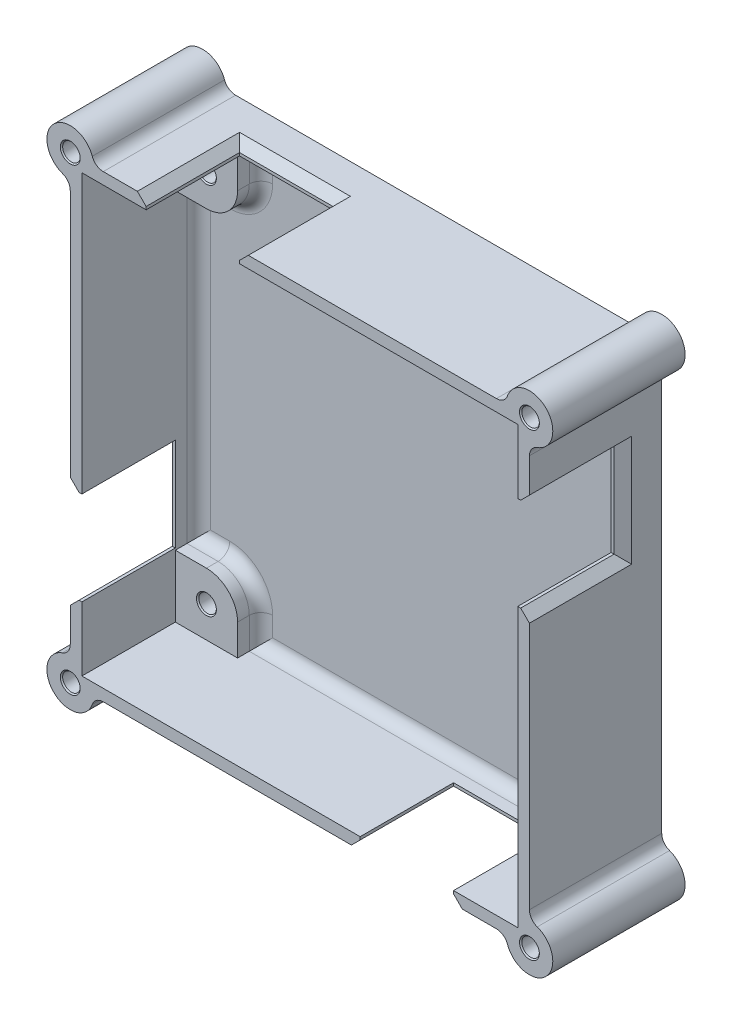
SolidWorks part; units mm, degrees
ref_plane "Front Plane" through (0, 0, 0) normal (0, 0, 1) x (1, 0, 0)
ref_plane "Top Plane" through (0, 0, 0) normal (0, 1, 0) x (1, 0, 0)
ref_plane "Right Plane" through (0, 0, 0) normal (1, 0, 0) x (0, 0, -1)
sketch "Sketch1" plane through (0, 0, 0) normal (0, 0, 1) x (1, 0, 0)
  line L1 (59, 59) -> (-59, 59)
  line L2 (59, 59) -> (59, -59)
  line L3 (59, -59) -> (-59, -59)
  line L4 (-59, 59) -> (-59, -59)
  line L5 (59, 59) -> (-59, -59) construction
  line L6 (59, -59) -> (-59, 59) construction
  point P0 (0, 0)
  dimension "D1" = 118
  dimension "D2" = 118
extrude "Boss-Extrude1" add sketch "Sketch1" against normal blind 4
sketch "Sketch2" plane through (0, 0, 0) normal (0, 0, 1) x (1, 0, 0)
  line L1 (56, 56) -> (-56, 56)
  line L2 (56, 56) -> (56, -56)
  line L3 (56, -56) -> (-56, -56)
  line L4 (-56, 56) -> (-56, -56)
  line L5 (56, 56) -> (-56, -56) construction
  line L6 (56, -56) -> (-56, 56) construction
  line L7 (59, 59) -> (-59, 59)
  line L8 (59, 59) -> (59, -59)
  line L9 (59, -59) -> (-59, -59)
  line L10 (-59, 59) -> (-59, -59)
  line L11 (59, 59) -> (-59, -59) construction
  line L12 (59, -59) -> (-59, 59) construction
  point P0 (0, 0)
  point P6 (0, 0)
  dimension "D1" = 112
  dimension "D2" = 112
extrude "Boss-Extrude2" add sketch "Sketch2" along normal blind 30
sketch "Sketch3" plane through (0, 0, 0) normal (0, 0, 1) x (1, 0, 0)
  line L7 (56, 56) -> (40, 56)
  line L8 (56, 56) -> (56, 40)
  line L9 (56, 40) -> (40, 40)
  line L10 (40, 56) -> (40, 40)
  line L11 (56, 56) -> (40, 40) construction
  line L12 (56, 40) -> (40, 56) construction
  circle A0 centre (48, 48) radius 2.25
  dimension "D1" = 4.5
  dimension "D2" = 48
  dimension "D3" = 48
  dimension "D4" = 16
  dimension "D5" = 16
extrude "Boss-Extrude3" add sketch "Sketch3" along normal blind 6
mirror "Mirror1" about plane through (0, 0, 0) normal (1, 0, 0) of "Boss-Extrude3" second plane through (0, 0, 0) second plane normal (0, 1, 0)
chamfer "Chamfer1" distance 0.3 angle 45 4 edges at (50.25, 48, 6) (50.25, -48, 6) (-50.25, 48, 6) (-50.25, -48, 6)
fillet "Fillet1" radius 8 4 edges at (40, 40, 3) (40, -40, 3) (-40, 40, 3) (-40, -40, 3)
sketch "Sketch7" plane through (0, 0, 30) normal (0, 0, 1) x (1, 0, 0)
  line L0 (56, -40) -> (56, 40) construction
  line L1 (59, 39.5) -> (56, 39.5)
  line L2 (59, 39.5) -> (59, 15.5)
  line L3 (59, 15.5) -> (56, 15.5)
  line L4 (56, 39.5) -> (56, 15.5)
  line L5 (59, 39.5) -> (56, 15.5) construction
  line L6 (59, 15.5) -> (56, 39.5) construction
  line L7 (59, 59) -> (-59, 59) construction
  line L8 (-15.5, 56) -> (-39.5, 56)
  line L9 (-15.5, 56) -> (-15.5, 59)
  line L10 (-15.5, 59) -> (-39.5, 59)
  line L11 (-39.5, 56) -> (-39.5, 59)
  line L12 (-15.5, 56) -> (-39.5, 59) construction
  line L13 (-15.5, 59) -> (-39.5, 56) construction
  line L14 (-59, 59) -> (-59, -59) construction
  line L15 (-56, -39.5) -> (-59, -39.5)
  line L16 (-56, -39.5) -> (-56, -15.5)
  line L17 (-56, -15.5) -> (-59, -15.5)
  line L18 (-59, -39.5) -> (-59, -15.5)
  line L19 (-56, -39.5) -> (-59, -15.5) construction
  line L20 (-56, -15.5) -> (-59, -39.5) construction
  line L21 (-56, -56) -> (56, -56) construction
  line L22 (39.5, -59) -> (15.5, -59)
  line L23 (39.5, -59) -> (39.5, -56)
  line L24 (39.5, -56) -> (15.5, -56)
  line L25 (15.5, -59) -> (15.5, -56)
  line L26 (39.5, -59) -> (15.5, -56) construction
  line L27 (39.5, -56) -> (15.5, -59) construction
  point P0 (57.5, 27.5)
  point P7 (-27.5, 57.5)
  point P15 (-57.5, -27.5)
  point P22 (27.5, -57.5)
  dimension "D1" = 3
  dimension "D2" = 24
  dimension "D3" = 27.5
  dimension "D4" = 24
  dimension "D5" = 27.5
  dimension "D6" = 3
  dimension "D7" = 24
  dimension "D8" = 3
  dimension "D9" = 27.5
  dimension "D10" = 24
  dimension "D11" = 3
  dimension "D12" = 27.5
extrude "Cut-Extrude1" cut sketch "Sketch7" against normal blind 24
chamfer "Chamfer3" distance 2.25 angle 45 12 edges at (-59, -39.5, 18) (-59, -15.5, 18) (-59, -27.5, 6) (-39.5, 59, 18) (-27.5, 59, 6) (-15.5, 59, 18) (59, 39.5, 18) (59, 27.5, 6) (59, 15.5, 18) (39.5, -59, 18) (27.5, -59, 6) (15.5, -59, 18)
sketch "Sketch8" plane through (0, 0, 30) normal (0, 0, 1) x (1, 0, 0)
  line L0 (53, 59) -> (59, 59)
  line L1 (59, 59) -> (59, 53)
  arc A1 (53, 59) -> (59, 53) centre (59, 59) cw
extrude "Boss-Extrude4" add sketch "Sketch8" against normal up to surface (34 mm away) up to face at (0, 0, -4)
sketch "Sketch9" plane through (0, 0, 30) normal (0, 0, 1) x (1, 0, 0)
  circle A0 centre (59, 59) radius 2.25
  dimension "D3" = 4.5
  dimension "D1" = 59
  dimension "D2" = 59
extrude "Cut-Extrude2" cut sketch "Sketch9" against normal blind 6 contours A0
mirror "Mirror2" about plane through (0, 0, 0) normal (1, 0, 0) of "Cut-Extrude2", "Boss-Extrude4" second plane through (0, 0, 0) second plane normal (0, 1, 0)
chamfer "Chamfer2" distance 0.3 angle 45 4 edges at (61.25, 59, 30) (61.25, -59, 30) (-61.25, 59, 30) (-61.25, -59, 30)
fillet "Fillet2" radius 3 16 edges at (-42.3431, 42.3431, 0) (-42.3431, -42.3431, 0) (42.3431, -42.3431, 0) (42.3431, 42.3431, 0) (0, 56, 0) (40, 52, 0) (52, 40, 0) (56, 0, 0) (52, -40, 0) (40, -52, 0) (-56, 0, 0) (-52, 40, 0) (-40, 52, 0) (0, -56, 0) (-40, -52, 0) (-52, -40, 0)
fillet "Fillet3" radius 3 8 edges at (53, 59, 13) (59, 53, 13) (59, -53, 13) (53, -59, 13) (-59, 53, 13) (-53, 59, 13) (-53, -59, 13) (-59, -53, 13)
equation "\"pcb_lw\"= 110mm"
equation "\"pcb_height\"= 25mm"
equation "\"side_clearance\"= 1mm"
equation "\"top_clearance\"= 5mm"
equation "\"case_inner_lw\"= \"pcb_lw\" + 2 * \"side_clearance\""
equation "\"wall_thickness\"= 3mm"
equation "\"base_thickness\"= 4mm"
equation "\"case_outer_lw\"= \"case_inner_lw\" + 2 * \"wall_thickness\""
equation "\"D1@Boss-Extrude1\"=\"base_thickness\""
equation "\"D1@Sketch2\"=\"case_inner_lw\""
equation "\"D2@Sketch2\" = \"case_inner_lw\""
equation "\"wall_height\"= \"pcb_height\" + \"top_clearance\""
equation "\"D1@Boss-Extrude2\"=\"wall_height\""
equation "\"m3_dia\"= 4.5mm"
equation "\"m3_height\"= 6mm"
equation "\"hole_inset\"= 7mm"
equation "\"hole_xy\"= \"pcb_lw\" / 2 - \"hole_inset\""
equation "\"D1@Sketch3\"=\"m3_dia\""
equation "\"m3_standoff_lw\"= ( \"case_inner_lw\" / 2 - \"hole_xy\" ) * 2"
equation "\"D2@Sketch3\"=\"hole_xy\""
equation "\"D3@Sketch3\" = \"hole_xy\""
equation "\"D1@Boss-Extrude3\"=\"m3_height\""
equation "\"D4@Sketch3\"=\"m3_standoff_lw\""
equation "\"D5@Sketch3\"=\"m3_standoff_lw\""
equation "\"m3_chamfer\"= 0.3mm"
equation "\"D1@Chamfer1\"=\"m3_chamfer\""
equation "\"conn_center\"= 27.5mm"
equation "\"conn_width\"= 24mm"
equation "\"D1@Sketch7\"=\"wall_thickness\""
equation "\"D2@Sketch7\"=\"conn_width\""
equation "\"D4@Sketch7\"=\"conn_width\""
equation "\"D5@Sketch7\"=\"conn_center\""
equation "\"D6@Sketch7\"=\"wall_thickness\""
equation "\"D7@Sketch7\"=\"conn_width\""
equation "\"D8@Sketch7\"=\"wall_thickness\""
equation "\"D9@Sketch7\"=\"conn_center\""
equation "\"D10@Sketch7\"=\"conn_width\""
equation "\"D11@Sketch7\"=\"wall_thickness\""
equation "\"D12@Sketch7\"=\"conn_center\""
equation "\"D1@Cut-Extrude1\"=\"wall_height\" - \"m3_height\""
equation "\"D2@Sketch1\"=\"case_outer_lw\""
equation "\"D1@Sketch1\"=\"case_outer_lw\""
equation "\"outer_standoff_dia\"= 12mm"
equation "\"D1@Sketch9\"=\"case_outer_lw\" / 2"
equation "\"D2@Sketch9\"=\"case_outer_lw\" / 2"
equation "\"D3@Sketch9\"=\"m3_dia\""
equation "\"D1@Chamfer2\"=\"m3_chamfer\""
equation "\"D1@Fillet1\"=\"m3_standoff_lw\" / 2"
equation "\"D1@Chamfer3\"=\"wall_thickness\" * 0.75"
equation "\"D1@Fillet2\"=\"m3_height\" / 2"
equation "\"D1@Fillet3\"=\"outer_standoff_dia\" / 4"
equation "\"D1@Fillet3\"= \"outer_standoff_dia\" / 4"
